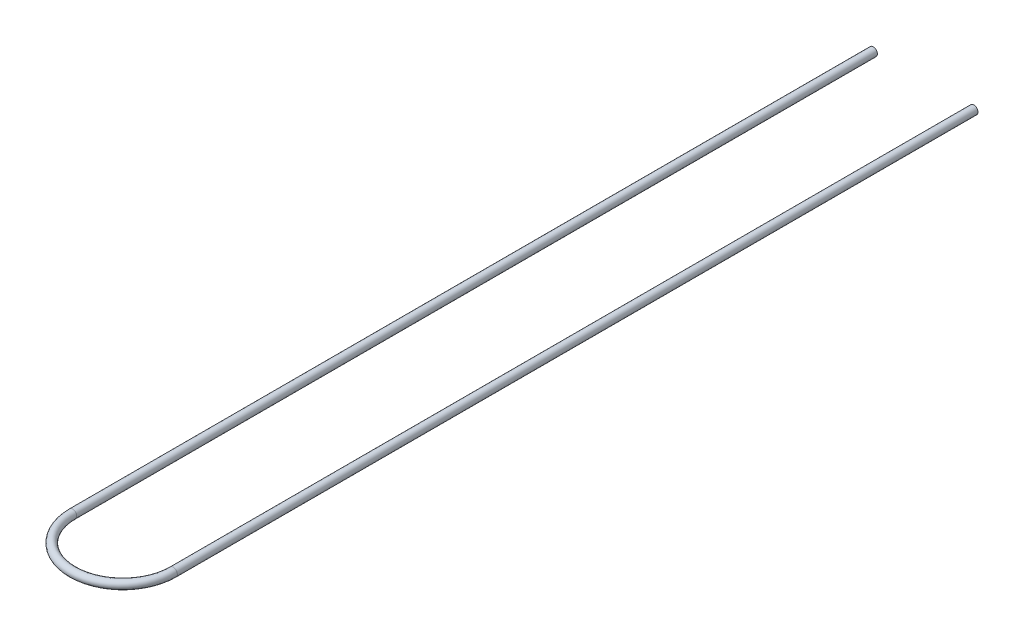
SolidWorks part; units mm, degrees
ref_plane "Front Plane" through (0, 0, 0) normal (0, 0, 1) x (1, 0, 0)
ref_plane "Top Plane" through (0, 0, 0) normal (0, 1, 0) x (1, 0, 0)
ref_plane "Right Plane" through (0, 0, 0) normal (1, 0, 0) x (0, 0, -1)
sketch "Sketch1" plane through (0, 0, 0) normal (0, 1, 0) x (1, 0, 0)
  line L0 (228.93, -300) -> (228.93, -2440)
  line L2 (-40, -300) -> (-40, -2440)
  arc A0 (-40, -2440) -> (228.93, -2440) centre (94.465, -2440) ccw
  dimension "D1" = 2140
  dimension "D2" = 268.93
ref_plane "Plane1" through (228.93, 0, 300) normal (0, 0, -1) x (-1, 0, 0)
sketch "Sketch2" plane through (228.93, 0, 300) normal (0, 0, -1) x (-1, 0, 0)
  circle A0 centre (0, 0) radius 9.95
  circle A1 centre (0, 0) radius 11.1
  dimension "D1" = 22.2
  dimension "D2" = 19.9
sweep "Sweep1" add profiles "Sketch2" path "Sketch1"
